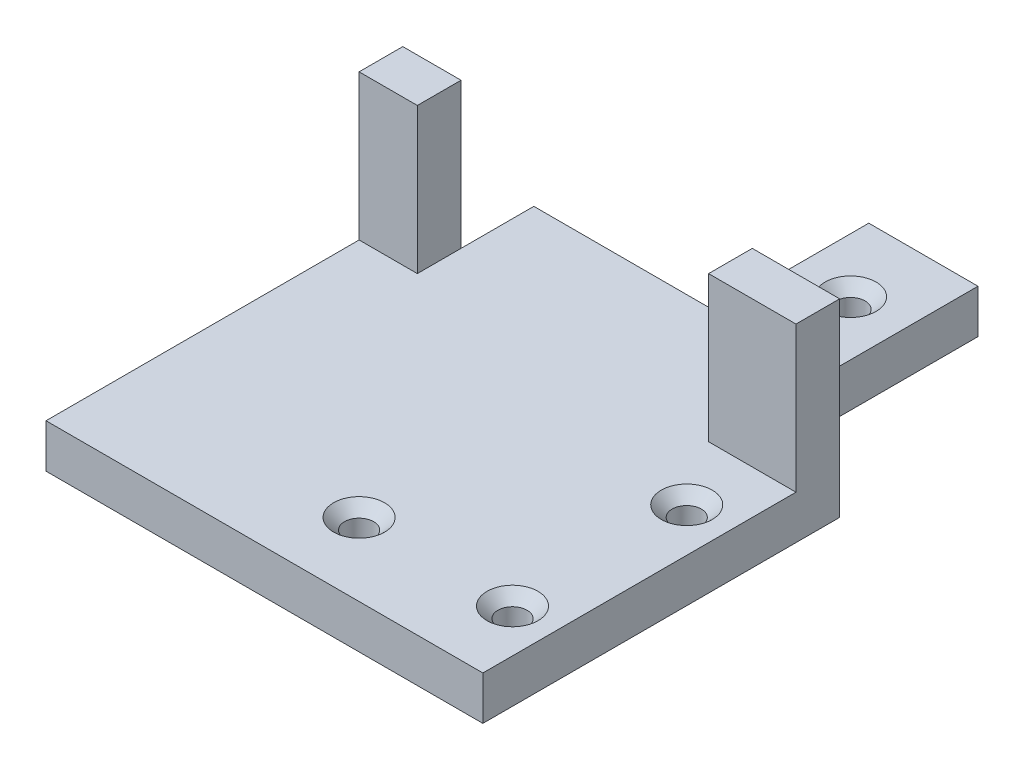
SolidWorks part; units mm, degrees
ref_plane "Front Plane" through (0, 0, 0) normal (0, 0, 1) x (1, 0, 0)
ref_plane "Top Plane" through (0, 0, 0) normal (0, 1, 0) x (1, 0, 0)
ref_plane "Right Plane" through (0, 0, 0) normal (1, 0, 0) x (0, 0, -1)
sketch "Sketch1" plane through (0, 0, 0) normal (0, 1, 0) x (1, 0, 0)
  line L1 (-30, -40) -> (30, -40)
  line L2 (-30, -40) -> (-30, 40)
  line L3 (-30, 40) -> (30, 40)
  line L4 (30, -40) -> (30, 40)
  line L5 (-30, -40) -> (30, 40) construction
  line L6 (-30, 40) -> (30, -40) construction
  point P0 (0, 0)
  dimension "D1" = 60
  dimension "D2" = 80
extrude "Boss-Extrude1" add sketch "Sketch1" along normal blind 6
sketch "Sketch2" plane through (0, 6, 0) normal (0, 1, 0) x (1, 0, 0)
  line L0 (-30, 9) -> (30, 9) construction
  line L1 (-22, -19) -> (18, -19) construction
  line L2 (-22, -19) -> (-22, 19) construction
  line L3 (-22, 19) -> (18, 19) construction
  line L4 (18, -19) -> (18, 19) construction
  line L5 (-22, -19) -> (18, 19) construction
  line L6 (-22, 19) -> (18, -19) construction
  line L7 (-30, 40) -> (-30, -40) construction
  line L8 (30, -40) -> (30, 40) construction
  line L9 (-40.8916, 9) -> (-22, 9)
  line L10 (-22, 9) -> (-22, 19)
  line L11 (-22, 19) -> (3, 19)
  line L12 (18, 9) -> (18, 40)
  line L13 (3, 19) -> (3, 40)
  line L14 (-30, -40) -> (30, -40) construction
  line L16 (18, 9) -> (35.9451, 9)
  line L17 (35.9451, 9) -> (35.9451, 57.3367)
  line L18 (35.9451, 57.3367) -> (-40.8916, 57.3367)
  line L19 (-40.8916, 57.3367) -> (-40.8916, 9)
  line L20 (30, 40) -> (-30, 40) construction
  line L21 (3, 40) -> (18, 40)
  circle A0 centre (3, -30) radius 2
  circle A1 centre (24.0716, -30) radius 2
  circle A2 centre (24, -6) radius 2
  circle A3 centre (10.5, 30) radius 2
  point P0 (-2, 0)
  point P14 (30, 0)
  dimension "D5" = 4
  dimension "D1" = 38
  dimension "D2" = 40
  dimension "D3" = 10
  dimension "D4" = 8
  dimension "D6" = 6
  dimension "D7" = 5.9284
  dimension "D8" = 10
  dimension "D9" = 25
  dimension "D10" = 15
  dimension "D11" = 15
  dimension "D12" = 7.5
  dimension "D13" = 10
extrude "Cut-Extrude1" cut sketch "Sketch2" against normal through all
sketch "Sketch3" plane through (0, 6, 0) normal (0, 1, 0) x (1, 0, 0)
  line L0 (-30, 9) -> (-30, -40) construction
  line L1 (30, 3) -> (18, 3)
  line L2 (30, 3) -> (30, 9)
  line L3 (30, 9) -> (18, 9)
  line L4 (18, 3) -> (18, 9)
  line L5 (30, 3) -> (18, 9) construction
  line L6 (30, 9) -> (18, 3) construction
  line L7 (-30, 3) -> (-22, 3)
  line L8 (-30, 3) -> (-30, 9)
  line L9 (-30, 9) -> (-22, 9)
  line L10 (-22, 3) -> (-22, 9)
  line L11 (-30, 3) -> (-22, 9) construction
  line L12 (-30, 9) -> (-22, 3) construction
  line L13 (30, -40) -> (30, 9) construction
  point P0 (24, 6)
  point P6 (-26, 6)
  dimension "D1" = 6
  dimension "D2" = 6
extrude "Boss-Extrude2" add sketch "Sketch3" along normal blind 20
chamfer "Chamfer1" distance 1.5 angle 45 4 edges at (10.5, 6, -28) (24, 6, 8) (24.0716, 6, 32) (3, 6, 32)
